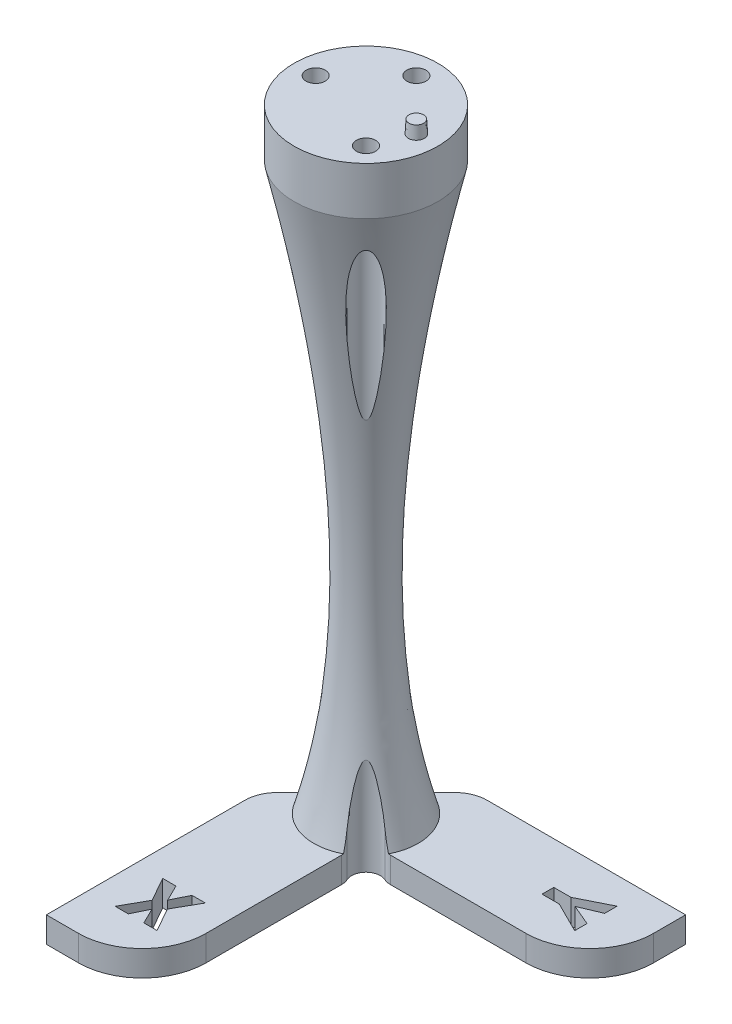
SolidWorks part; units mm, degrees
material "Полиуретановый жесткий пенопласт"
ref_plane "Спереди" through (0, 0, 0) normal (0, 0, 1) x (1, 0, 0)
ref_plane "Сверху" through (0, 0, 0) normal (0, 1, 0) x (1, 0, 0)
ref_plane "Справа" through (0, 0, 0) normal (1, 0, 0) x (0, 0, -1)
sketch "Эскиз1" plane through (0, 0, 0) normal (0, 1, 0) x (1, 0, 0)
  circle A0 centre (0, 0) radius 22.5
  circle A2 centre (0, 0) radius 15.75 construction
  dimension "D1" = 45
  dimension "D3" = 31.5
extrude "Бобышка-Вытянуть1" add sketch "Эскиз1" against normal blind 200
sketch "Эскиз2" plane through (0, -200, 0) normal (0, -1, 0) x (1, 0, 0)
  line L0 (-22.5, -22.5) -> (-22.5, 77.5)
  line L9 (77.5, -22.5) -> (-22.5, -22.5)
  line L11 (-12.5, 77.5) -> (-22.5, 77.5)
  line L13 (77.5, -12.5) -> (77.5, -22.5)
  line L14 (-22.5, -7.5) -> (49.4343, -7.5) construction
  line L15 (-7.5, -22.5) -> (-7.5, 49.4343) construction
  line L16 (-22.5, 49.4343) -> (7.5, 49.4343) construction
  line L17 (49.4343, 7.5) -> (49.4343, -22.5) construction
  line L18 (27.5, 7.5) -> (57.5, 7.5)
  line L19 (7.5, 27.5) -> (7.5, 57.5)
  circle A0 centre (0, 0) radius 22.5 construction
  arc A1 (7.5, 27.5) -> (27.5, 7.5) centre (27.5, 27.5) ccw
  arc A2 (-12.5, 77.5) -> (7.5, 57.5) centre (-12.5, 57.5) cw
  arc A3 (77.5, -12.5) -> (57.5, 7.5) centre (57.5, -12.5) ccw
  circle A4 centre (0, 0) radius 50 construction
  text T0 "X" font "Roboto Black" height 15
  text T1 "Y" font "Roboto Black" height 15
  point P12 (7.5, 77.5)
  point P15 (77.5, 7.5)
  dimension "D5" = 20
  dimension "D6" = 15
  dimension "D8" = 100
  dimension "D1" = 100
  dimension "D2" = 100
  dimension "D3" = 30
  dimension "D4" = 30
  dimension "D7" = 15
extrude "Бобышка-Вытянуть2" add sketch "Эскиз2" against normal blind 8
sketch "Эскиз3" plane through (0, 0, 0) normal (0, 1, 0) x (1, 0, 0)
  circle A0 centre (0, 0) radius 15.75 construction
  circle A1 centre (0, 0) radius 15.75 construction
  circle A2 centre (15.75, 0) radius 2.5
  dimension "D1" = 5
extrude "Бобышка-Вытянуть3" add sketch "Эскиз3" along normal blind 4 draft 3
sketch "Эскиз4" plane through (0, 0, 0) normal (0, 1, 0) x (1, 0, 0)
  line L0 (0, 0) -> (11.1369, -11.1369) construction
  line L1 (0, 0) -> (-15.75, 0) construction
  circle A1 centre (0, 0) radius 15.75 construction
  circle A3 centre (-15.75, 0) radius 3
  circle A5 centre (0, 15.75) radius 3
  circle A8 centre (11.1369, -11.1369) radius 3
  point P22 (0, 0)
  dimension "D1" = 6
  dimension "D3" = 6
  dimension "D4" = 6
  dimension "D2" = 135
extrude "Вырез-Вытянуть1" cut sketch "Эскиз4" against normal through all
ref_plane "Плоскость4" through (0, -10, 0) normal (0, 1, 0) x (1, 0, 0)
sketch "Эскиз5" plane through (0, -10, 0) normal (0, 1, 0) x (1, 0, 0)
  circle A0 centre (-15.75, 0) radius 4.5
  circle A1 centre (11.1369, -11.1369) radius 4.5
  circle A2 centre (0, 15.75) radius 4.5
  circle A3 centre (0, 0) radius 15.75 construction
  dimension "D1" = 9
  dimension "D2" = 9
  dimension "D3" = 9
extrude "Вырез-Вытянуть2" cut sketch "Эскиз5" against normal through all
ref_plane "Плоскость5" through (0, -15, 0) normal (0, 1, 0) x (1, 0, 0)
sketch "Эскиз8" plane through (0, 0, 0) normal (1, 0, 0) x (0, 0, -1)
  line L0 (-20.763, -192) -> (-27.5, -192) construction
  line L1 (-16.3209, -192) -> (-27.5, -192)
  line L2 (-22.5, -15) -> (3.0111, -126.3835) construction
  line L3 (3.0111, -126.3835) -> (-16.3209, -192) construction
  line L6 (24.75, -15) -> (-24.75, -15) construction
  line L7 (-22.5, 0) -> (-22.5, -192) construction
  line L8 (-16.3209, -192) -> (-22.9571, -192)
  line L9 (-22.9571, -192) -> (-22.5, -15)
  line L10 (0, 0) -> (0, -110.7575) construction
  spline S0 degree 2 poles (-22.5, -15) (3.0111, -126.3835) (-16.3209, -192) knots 0 0 0 1 1 1
  point P4 (7.0561, -176.6297)
  point P14 (-16.3209, -192)
  point P15 (3.0111, -126.3835)
revolve "Вырез-Повернуть1" cut sketch "Эскиз8" angle 360 about L10
ref_plane "Плоскость6" through (0, -175, 0) normal (0, -1, 0) x (-1, 0, 0)
sketch "Эскиз9" plane through (0, -175, 0) normal (0, -1, 0) x (-1, 0, 0)
  line L0 (5.6636, 16.9136) -> (9.7855, 21.0355)
  line L1 (22.5, 22.5) -> (-77.5, 22.5) construction
  line L2 (-5.6636, 16.9136) -> (-8.3211, 19.5711)
  line L5 (13.3211, 22.5) -> (-15.3921, 22.5)
  line L6 (0, 0) -> (-11.1369, -11.1369) construction
  line L7 (22.5, 13.3211) -> (22.5, -15.3921)
  line L8 (16.9136, -5.6636) -> (19.5711, -8.3211)
  line L9 (16.9136, 5.6636) -> (21.0355, 9.7855)
  line L10 (-7.5, -27.5) -> (-7.5, -57.5) construction
  line L11 (-57.5, -7.5) -> (-27.5, -7.5) construction
  line L12 (-7.5, -15.0934) -> (-7.5, -57.5)
  line L13 (-57.5, -7.5) -> (-15.0934, -7.5)
  line L14 (-7.5, -57.5) -> (-57.5, -7.5)
  arc A0 (-4.3575, 14.6264) -> (4.3575, 14.6264) centre (0, 15.75) ccw
  arc A2 (-7.0458, -13.011) -> (-13.011, -7.0458) centre (-11.1369, -11.1369) ccw
  circle A3 centre (-11.1369, -11.1369) radius 4.5 construction
  circle A4 centre (-11.1369, -11.1369) radius 4.5 construction
  circle A5 centre (0, 15.75) radius 4.5 construction
  arc A7 (13.3211, 22.5) -> (9.7855, 21.0355) centre (13.3211, 17.5) ccw
  arc A8 (-15.3921, 22.5) -> (-8.3211, 19.5711) centre (-15.3921, 12.5) cw
  arc A9 (-5.6636, 16.9136) -> (-4.3575, 14.6264) centre (-9.1991, 13.3781) cw
  arc A10 (5.6636, 16.9136) -> (4.3575, 14.6264) centre (9.1991, 13.3781) ccw
  arc A11 (16.9136, 5.6636) -> (14.6264, 4.3575) centre (13.3781, 9.1991) cw
  arc A12 (16.9136, -5.6636) -> (14.6264, -4.3575) centre (13.3781, -9.1991) ccw
  arc A13 (22.5, -15.3921) -> (19.5711, -8.3211) centre (12.5, -15.3921) ccw
  arc A14 (22.5, 13.3211) -> (21.0355, 9.7855) centre (17.5, 13.3211) cw
  arc A15 (14.6264, -4.3575) -> (14.6264, 4.3575) centre (15.75, 0) cw
  arc A16 (-15.0934, -7.5) -> (-13.011, -7.0458) centre (-15.0934, -2.5) ccw
  arc A17 (-7.0458, -13.011) -> (-7.5, -15.0934) centre (-2.5, -15.0934) ccw
  point P4 (-4.5, 15.75)
  point P22 (4.5, 15.75)
  point P43 (15.75, 4.5)
  point P44 (15.75, -4.5)
  dimension "D3" = 5
  dimension "D4" = 10
  dimension "D5" = 5
  dimension "D6" = 5
  dimension "D7" = 5
  dimension "D8" = 5
  dimension "D1" = 45
  dimension "D2" = 45
extrude "Вырез-Вытянуть4" cut sketch "Эскиз9" along normal through all
